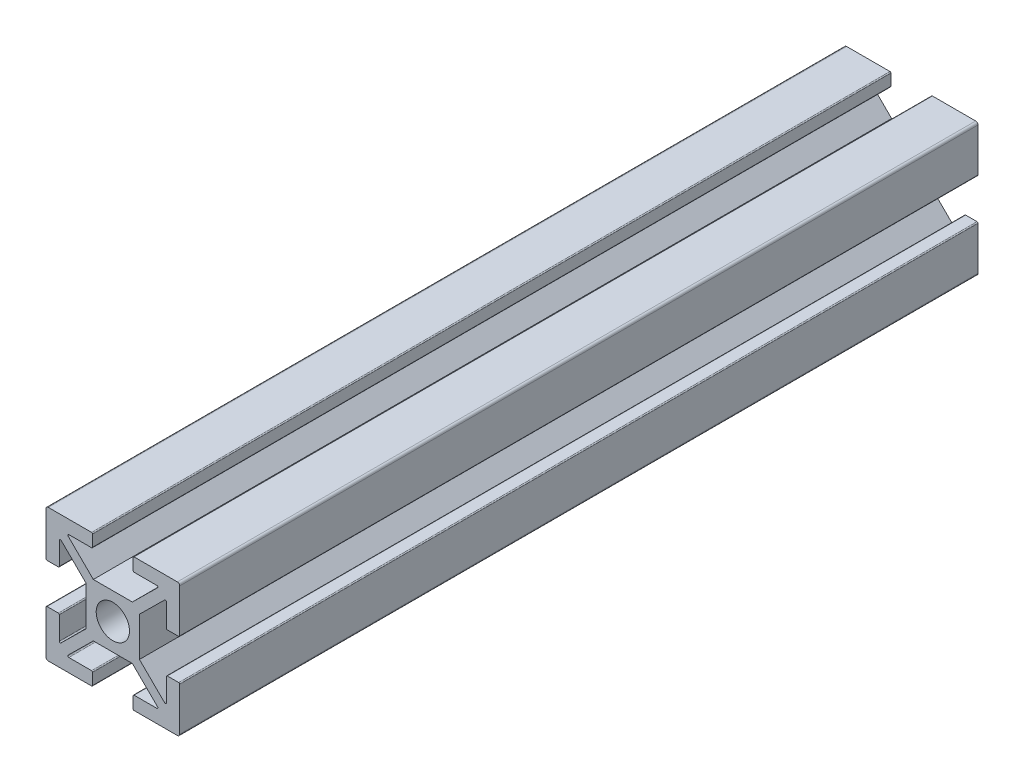
SolidWorks part; units mm, degrees
ref_plane "Front Plane" through (0, 0, 0) normal (0, 0, 1) x (1, 0, 0)
ref_plane "Top Plane" through (0, 0, 0) normal (0, 1, 0) x (1, 0, 0)
ref_plane "Right Plane" through (0, 0, 0) normal (1, 0, 0) x (0, 0, -1)
sketch "Sketch1" plane through (0, 0, 0) normal (0, 0, 1) x (1, 0, 0)
  line L0 (-7.4274, 2.1557) -> (-5.7274, 2.1557)
  line L1 (-0.7274, 9.1557) -> (-7.2274, 9.1557)
  line L2 (-7.5774, 2.3057) -> (-7.5774, 8.8057)
  line L3 (5.4021, 3.1557) -> (-0.4643, 3.1557)
  line L4 (-1.5311, -3.7897) -> (-1.5311, 2.1011)
  line L5 (-5.5774, 2.3057) -> (-5.5774, 5.7419)
  line L6 (-4.1455, 7.1557) -> (-0.7274, 7.1557)
  line L7 (-0.5774, 7.3057) -> (-0.5774, 9.0057)
  line L8 (-5.5774, 7.1557) -> (-1.5311, 3.1557) construction
  line L9 (-5.3219, 5.8486) -> (-1.5311, 2.1011)
  line L10 (-4.2509, 6.899) -> (-0.4643, 3.1557)
  line L11 (10.5152, 7.1557) -> (6.4689, 3.1557) construction
  line L12 (2.4689, -0.8443) -> (2.4689, 10.8443) construction
  line L13 (2.4689, -0.8443) -> (-12.5152, -0.8443) construction
  line L14 (9.1887, 6.899) -> (5.4021, 3.1557)
  line L15 (10.2598, 5.8486) -> (6.4689, 2.1011)
  line L16 (5.5152, 7.3057) -> (5.5152, 9.0057)
  line L17 (9.0833, 7.1557) -> (5.6652, 7.1557)
  line L18 (10.5152, 2.3057) -> (10.5152, 5.7419)
  line L19 (6.4689, -3.7897) -> (6.4689, 2.1011)
  line L20 (12.5152, 2.3057) -> (12.5152, 8.8057)
  line L21 (5.6652, 9.1557) -> (12.1652, 9.1557)
  line L22 (12.3652, 2.1557) -> (10.6652, 2.1557)
  line L23 (10.5152, -8.8443) -> (6.4689, -4.8443) construction
  line L24 (-5.5774, -8.8443) -> (-1.5311, -4.8443) construction
  line L25 (12.3652, -3.8443) -> (10.6652, -3.8443)
  line L26 (5.6652, -10.8443) -> (12.1652, -10.8443)
  line L27 (12.5152, -3.9943) -> (12.5152, -10.4943)
  line L28 (10.5152, -3.9943) -> (10.5152, -7.4305)
  line L29 (9.0833, -8.8443) -> (5.6652, -8.8443)
  line L30 (5.5152, -8.9943) -> (5.5152, -10.6943)
  line L31 (10.2598, -7.5372) -> (6.4689, -3.7897)
  line L32 (9.1887, -8.5876) -> (5.4021, -4.8443)
  line L33 (-4.2509, -8.5876) -> (-0.4643, -4.8443)
  line L34 (-5.3219, -7.5372) -> (-1.5311, -3.7897)
  line L35 (-0.5774, -8.9943) -> (-0.5774, -10.6943)
  line L36 (-4.1455, -8.8443) -> (-0.7274, -8.8443)
  line L37 (-5.5774, -3.9943) -> (-5.5774, -7.4305)
  line L38 (5.4021, -4.8443) -> (-0.4643, -4.8443)
  line L39 (-7.5774, -3.9943) -> (-7.5774, -10.4943)
  line L40 (-0.7274, -10.8443) -> (-7.2274, -10.8443)
  line L41 (-7.4274, -3.8443) -> (-5.7274, -3.8443)
  circle A0 centre (2.4689, -0.8443) radius 2.5
  arc A1 (-7.5774, 8.8057) -> (-7.2274, 9.1557) centre (-7.2274, 8.8057) cw
  arc A2 (-7.4274, 2.1557) -> (-7.5774, 2.3057) centre (-7.4274, 2.3057) cw
  arc A3 (-5.7274, 2.1557) -> (-5.5774, 2.3057) centre (-5.7274, 2.3057) ccw
  arc A4 (-0.7274, 9.1557) -> (-0.5774, 9.0057) centre (-0.7274, 9.0057) cw
  arc A5 (-0.7274, 7.1557) -> (-0.5774, 7.3057) centre (-0.7274, 7.3057) ccw
  arc A6 (-4.2509, 6.899) -> (-4.1455, 7.1557) centre (-4.1455, 7.0057) cw
  arc A7 (-5.3219, 5.8486) -> (-5.5774, 5.7419) centre (-5.4274, 5.7419) ccw
  arc A8 (10.2598, 5.8486) -> (10.5152, 5.7419) centre (10.3652, 5.7419) cw
  arc A9 (9.1887, 6.899) -> (9.0833, 7.1557) centre (9.0833, 7.0057) ccw
  arc A10 (5.6652, 7.1557) -> (5.5152, 7.3057) centre (5.6652, 7.3057) cw
  arc A11 (5.6652, 9.1557) -> (5.5152, 9.0057) centre (5.6652, 9.0057) ccw
  arc A12 (10.6652, 2.1557) -> (10.5152, 2.3057) centre (10.6652, 2.3057) cw
  arc A13 (12.3652, 2.1557) -> (12.5152, 2.3057) centre (12.3652, 2.3057) ccw
  arc A14 (12.5152, 8.8057) -> (12.1652, 9.1557) centre (12.1652, 8.8057) ccw
  arc A15 (12.5152, -10.4943) -> (12.1652, -10.8443) centre (12.1652, -10.4943) cw
  arc A16 (12.3652, -3.8443) -> (12.5152, -3.9943) centre (12.3652, -3.9943) cw
  arc A17 (10.6652, -3.8443) -> (10.5152, -3.9943) centre (10.6652, -3.9943) ccw
  arc A18 (5.6652, -10.8443) -> (5.5152, -10.6943) centre (5.6652, -10.6943) cw
  arc A19 (5.6652, -8.8443) -> (5.5152, -8.9943) centre (5.6652, -8.9943) ccw
  arc A20 (9.1887, -8.5876) -> (9.0833, -8.8443) centre (9.0833, -8.6943) cw
  arc A21 (10.2598, -7.5372) -> (10.5152, -7.4305) centre (10.3652, -7.4305) ccw
  arc A22 (-5.3219, -7.5372) -> (-5.5774, -7.4305) centre (-5.4274, -7.4305) cw
  arc A23 (-4.2509, -8.5876) -> (-4.1455, -8.8443) centre (-4.1455, -8.6943) ccw
  arc A24 (-0.7274, -8.8443) -> (-0.5774, -8.9943) centre (-0.7274, -8.9943) cw
  arc A25 (-0.7274, -10.8443) -> (-0.5774, -10.6943) centre (-0.7274, -10.6943) ccw
  arc A26 (-5.7274, -3.8443) -> (-5.5774, -3.9943) centre (-5.7274, -3.9943) cw
  arc A27 (-7.4274, -3.8443) -> (-7.5774, -3.9943) centre (-7.4274, -3.9943) ccw
  arc A28 (-7.5774, -10.4943) -> (-7.2274, -10.8443) centre (-7.2274, -10.4943) ccw
  point P27 (5.5152, 7.1557)
  point P28 (12.5152, -10.8443)
  point P47 (6.4689, -0.8443)
  point P57 (2.4689, 3.1557)
  point P59 (5.5152, 9.1557)
  point P60 (10.5152, 2.1557)
  point P61 (12.5152, 2.1557)
  point P62 (12.5152, 9.1557)
  point P112 (-1.5311, -0.8443)
  point P113 (12.5152, -3.8443)
  point P114 (10.5152, -3.8443)
  point P115 (5.5152, -10.8443)
  point P116 (2.4689, -4.8443)
  point P117 (-0.5774, -8.8443)
  point P118 (-0.5774, -10.8443)
  point P119 (-5.5774, -3.8443)
  point P120 (5.5152, -8.8443)
  point P121 (-7.5774, -3.8443)
  point P122 (-7.5774, -10.8443)
  dimension "D3" = 0.35
  dimension "D4" = 0.15
  dimension "D5" = 0.15
  dimension "D6" = 0.15
  dimension "D7" = 0.15
  dimension "D8" = 0.15
  dimension "D9" = 0.15
  dimension "D1" = 0.75
  dimension "D2" = 0.75
extrude "Boss-Extrude1" add sketch "Sketch1" along normal blind 120
